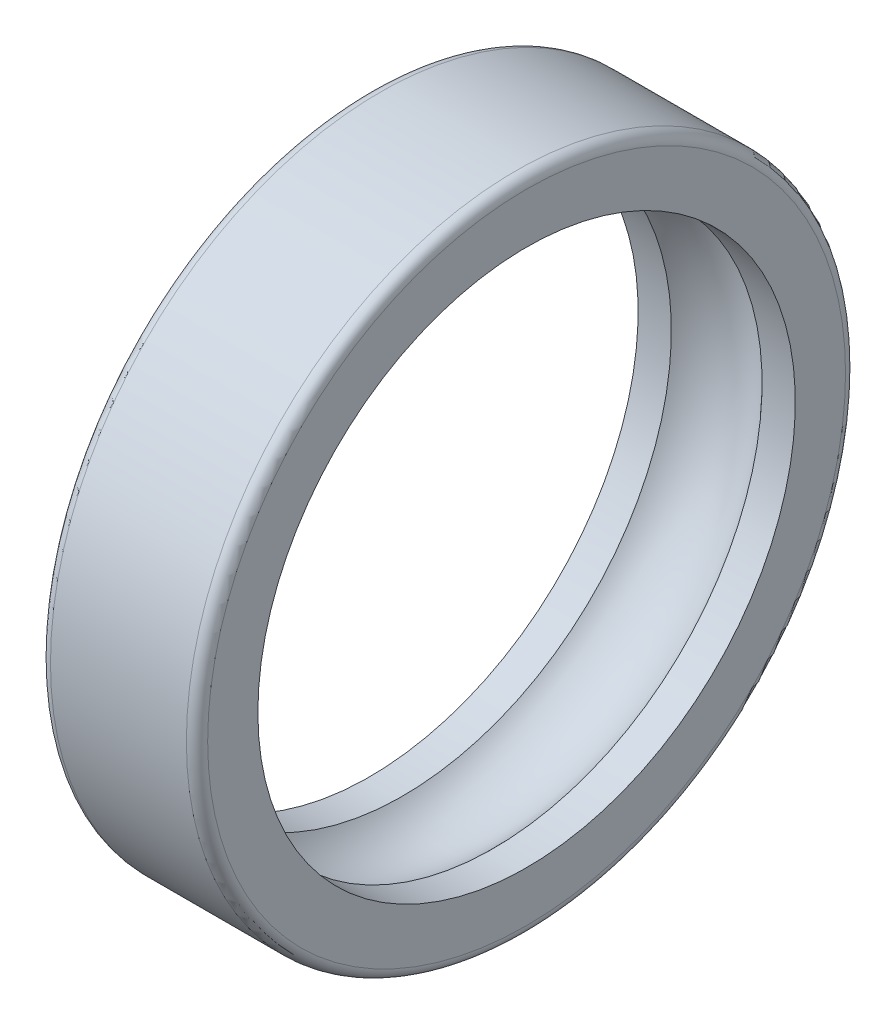
SolidWorks part; units mm, degrees
ref_plane "Front Plane" through (0, 0, 0) normal (0, 0, 1) x (1, 0, 0)
ref_plane "Top Plane" through (0, 0, 0) normal (0, 1, 0) x (1, 0, 0)
ref_plane "Right Plane" through (0, 0, 0) normal (1, 0, 0) x (0, 0, -1)
sketch "Sketch1" plane through (0, 0, 0) normal (0, 0, 1) x (1, 0, 0)
  line L0 (-45.2666, 0) -> (59.3683, 0) construction
  line L1 (0, 59) -> (0, 0) construction
  line L2 (-15.5, 65) -> (15.5, 65)
  line L3 (-15.5, 65) -> (-15.5, 53)
  line L4 (-15.5, 53) -> (-8.9443, 53)
  line L5 (15.5, 65) -> (15.5, 53)
  line L6 (-15.5, 65) -> (15.5, 53) construction
  line L7 (-15.5, 53) -> (15.5, 65) construction
  line L8 (8.9443, 53) -> (15.5, 53)
  arc A0 (8.9443, 53) -> (-8.9443, 53) centre (0, 45) ccw
  point P3 (0, 59)
  dimension "D4" = 24
  dimension "D1" = 53
  dimension "D2" = 65
  dimension "D3" = 31
  dimension "D5" = 8
revolve "Revolve1" add sketch "Sketch1" angle 360 about L0
fillet "Fillet1" radius 2.1 2 edges at (15.5, 0, 65) (-15.5, 0, 65)
